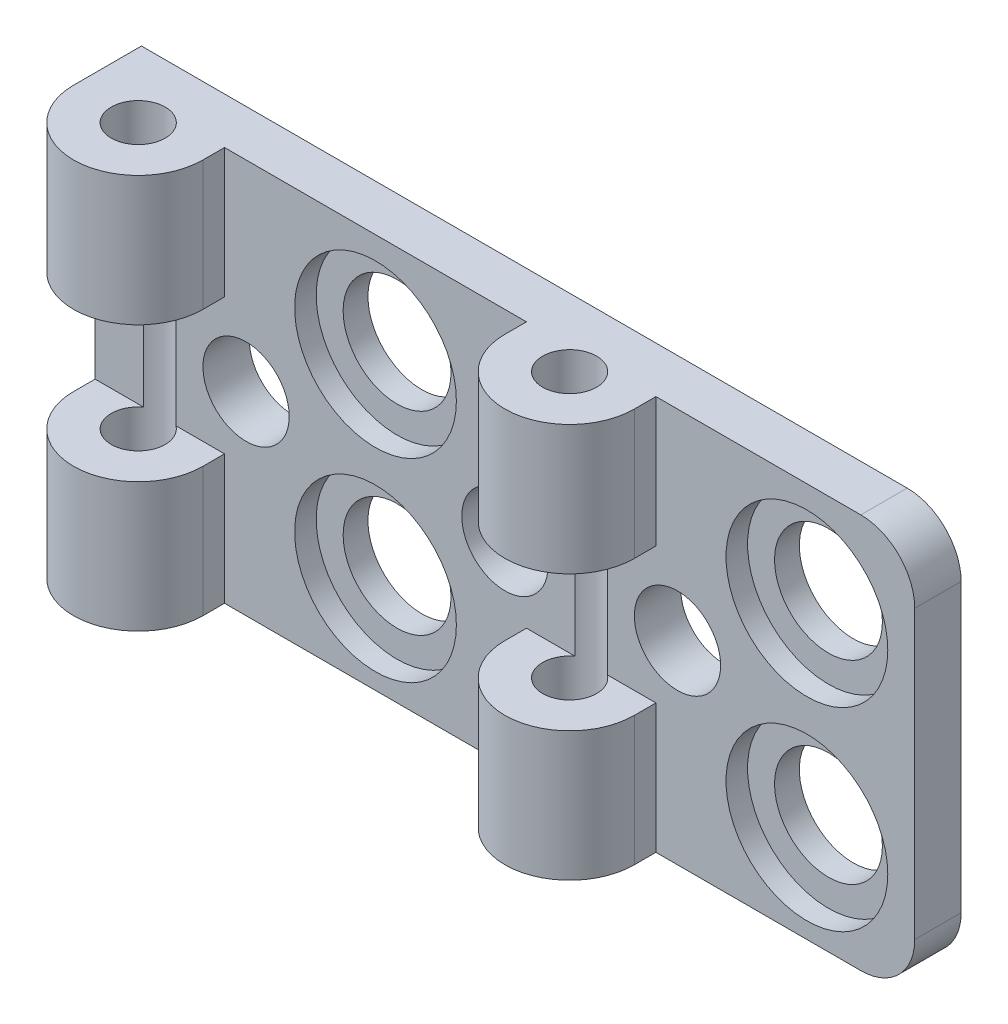
SolidWorks part; units mm, degrees
ref_plane "Front Plane" through (0, 0, 0) normal (0, 0, 1) x (1, 0, 0)
ref_plane "Top Plane" through (0, 0, 0) normal (0, 1, 0) x (1, 0, 0)
ref_plane "Right Plane" through (0, 0, 0) normal (1, 0, 0) x (0, 0, -1)
sketch "Sketch1" plane through (0, 0, 0) normal (0, 1, 0) x (1, 0, 0)
  circle A0 centre (0, 0) radius 2.5 construction
  circle A1 centre (-40, 0) radius 2.5 construction
  circle A2 centre (-40, 0) radius 2.501
  circle A3 centre (0, 0) radius 2.501
  circle A4 centre (-40, 0) radius 6
  circle A5 centre (0, 0) radius 6
  dimension "D2" = 5
  dimension "D4" = 12
  dimension "D5" = 5.002
  dimension "D6" = 3.499
  dimension "D1" = 40
  dimension "D3" = 0.001
extrude "Boss-Extrude1" add sketch "Sketch1" along normal blind 36.6 contours A4 A2 | A5 A3
sketch "Sketch2" plane through (0, 0, 0) normal (0, 0, 1) x (1, 0, 0)
  line L0 (-20, 27) -> (-20, 9) construction
  line L1 (-20, 18) -> (-7.7491, 18) construction
  circle A0 centre (-20, 27) radius 7.5
  circle A1 centre (-20, 27) radius 5
  circle A2 centre (20, 27) radius 7.5
  circle A3 centre (20, 27) radius 5
  circle A4 centre (20, 9) radius 5
  circle A5 centre (20, 9) radius 7.5
  circle A6 centre (-20, 9) radius 5
  circle A7 centre (-20, 9) radius 7.5
  dimension "D1" = 10
  dimension "D2" = 15
  dimension "D3" = 40
  dimension "D4" = 18
  dimension "D5" = 18
  dimension "D6" = 20
sketch "Sketch3" plane through (0, 0, 0) normal (0, 1, 0) x (1, 0, 0)
  line L0 (-46, 0) -> (-46, 21.9457) construction
  line L1 (-34, 4) -> (-6, 4)
  line L2 (-46, 0) -> (-46, 6.3)
  line L3 (-46, 6.3) -> (6, 6.3)
  line L4 (6, 0) -> (6, 4)
  line L5 (6, 0) -> (6, 22.9377) construction
  line L6 (-6, 0) -> (-6, 4)
  line L7 (-34, 0) -> (-34, 4) construction
  line L8 (-34, 0) -> (-34, 4)
  line L9 (6, 4) -> (30, 4)
  line L10 (30, 4) -> (30, 6.3)
  line L11 (30, 6.3) -> (6, 6.3)
  circle A0 centre (-40, 0) radius 6 construction
  circle A1 centre (0, 0) radius 6 construction
  arc A2 (-46, 0) -> (-34, 0) centre (-40, 0) ccw
  arc A3 (-6, 0) -> (6, 0) centre (0, 0) ccw
  circle A4 centre (-40, 0) radius 6 construction
  circle A5 centre (-40, 0) radius 6
  circle A6 centre (0, 0) radius 6 construction
  arc A7 (-6, 0) -> (6, 0) centre (0, 0) ccw
  arc A8 (-6, 0) -> (6, 0) centre (0, 0) ccw
  circle A9 centre (0, 0) radius 6
  dimension "D1" = 2.3
  dimension "D2" = 4
  dimension "D3" = 24
extrude "Boss-Extrude2" add sketch "Sketch3" along normal up to surface (36.6 mm away) up to face at (0, 36.6, 2.501)
extrude "Cut-Extrude1" cut sketch "Sketch2" against normal through all contours A1 | A6 | A3 | A4
sketch "Sketch6" plane through (0, 0, -4) normal (0, 0, 1) x (1, 0, 0)
  line L0 (-20, 27) -> (-20, 9) construction
  line L1 (-20, 18) -> (-27.0715, 18) construction
  line L4 (-6, 36.6) -> (-34, 36.6)
  line L5 (-34, 36.6) -> (-34, 0)
  line L6 (-34, 0) -> (-6, 0)
  line L7 (-6, 0) -> (-6, 36.6)
  line L8 (-6, 36.6) -> (-34, 36.6)
  line L9 (-34, 36.6) -> (-34, 0)
  line L10 (-34, 0) -> (-6, 0)
  line L11 (-6, 0) -> (-6, 36.6)
  line L12 (30, 36.6) -> (6, 36.6)
  line L13 (6, 36.6) -> (6, 0)
  line L14 (6, 0) -> (30, 0)
  line L15 (30, 0) -> (30, 36.6)
  line L16 (30, 36.6) -> (6, 36.6)
  line L17 (6, 36.6) -> (6, 0)
  line L18 (6, 0) -> (30, 0)
  line L19 (30, 0) -> (30, 36.6)
  circle A11 centre (-20, 27) radius 7.5
  circle A12 centre (-20, 27) radius 7.5
  circle A14 centre (-20, 9) radius 7.5
  circle A15 centre (-20, 9) radius 7.5
  circle A17 centre (20, 27) radius 7.5
  circle A18 centre (20, 27) radius 7.5
  circle A20 centre (20, 9) radius 7.5
  circle A21 centre (20, 9) radius 7.5
  dimension "D7" = 15
  dimension "D1" = 0
  dimension "D2" = 2.5
  dimension "D3" = 2.5
  dimension "D4" = 2.5
  dimension "D5" = 2.5
  dimension "D6" = 0
extrude "Boss-Extrude3" add sketch "Sketch6" along normal blind 2 contours A12
fillet "Fillet2" radius 5 2 edges at (30, 36.6, -4.15) (30, 0, -4.15)
sketch "Sketch7" plane through (0, 0, -2) normal (0, 0, 1) x (1, 0, 0)
  line L0 (-20, 27) -> (-20, 9) construction
  line L1 (-20, 18) -> (-32, 18) construction
  line L2 (8, 18) -> (20, 18) construction
  line L3 (20, 27) -> (20, 9) construction
  circle A0 centre (-32, 18) radius 4
  circle A1 centre (-8, 18) radius 4
  circle A2 centre (8, 18) radius 4
  dimension "D2" = 8
  dimension "D1" = 24
extrude "Cut-Extrude2" cut sketch "Sketch7" against normal through all contours A0
sketch "Sketch8" plane through (0, 0, -2) normal (0, 0, 1) x (1, 0, 0)
  line L0 (-6, 0) -> (-6, 14.5359) construction
  line L1 (-6, 24.6) -> (6, 24.6)
  line L2 (-6, 24.6) -> (-6, 12)
  line L3 (-6, 12) -> (6, 12)
  line L4 (6, 24.6) -> (6, 12)
  line L5 (6, 36.6) -> (6, 21.4641) construction
  line L6 (-34, 36.6) -> (-34, 21.4641) construction
  line L7 (-34, 24.6) -> (-46, 24.6)
  line L8 (-34, 24.6) -> (-34, 12)
  line L9 (-34, 12) -> (-46, 12)
  line L10 (-46, 24.6) -> (-46, 12)
  line L11 (-46, 36.6) -> (-46, 0) construction
  line L12 (-46, 36.6) -> (-46, 0) construction
  line L13 (-46, 18.3) -> (32.8031, 18.3) construction
  line L15 (-6, 36.6) -> (-34, 36.6) construction
  dimension "D1" = 12
extrude "Cut-Extrude3" cut sketch "Sketch8" along normal through all
equation "\"D4@Sketch6\"=\"D2@Sketch6\""
equation "\"D5@Sketch6\"=\"D2@Sketch6\""
equation "\"D3@Sketch6\"=\"D2@Sketch6\""
